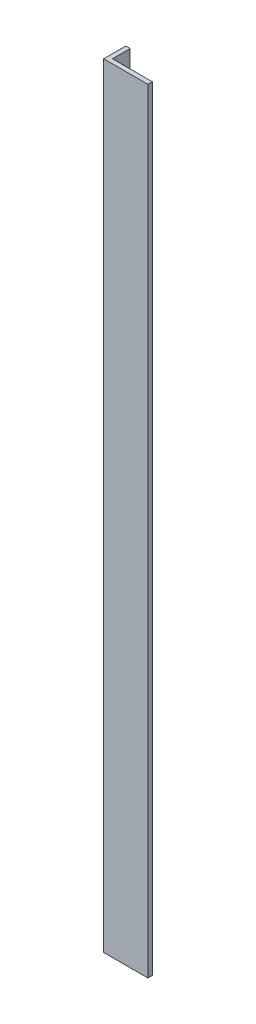
SolidWorks part; units mm, degrees
ref_plane "Front Plane" through (0, 0, 0) normal (0, 0, 1) x (1, 0, 0)
ref_plane "Top Plane" through (0, 0, 0) normal (0, 1, 0) x (1, 0, 0)
ref_plane "Right Plane" through (0, 0, 0) normal (1, 0, 0) x (0, 0, -1)
sketch "Sketch1" plane through (0, 0, 0) normal (0, 1, 0) x (1, 0, 0)
  line L0 (0, 0) -> (0, 10)
  line L1 (0, 10) -> (2, 10)
  line L2 (2, 10) -> (2, 2)
  line L3 (2, 2) -> (20, 2)
  line L4 (20, 2) -> (20, 0)
  line L5 (20, 0) -> (0, 0)
extrude "Boss-Extrude1" add sketch "Sketch1" along normal blind 300 and the other way up to surface (50 mm away)
hole_wizard "Ø3.0 (3) Diameter Hole3" positions "Sketch6" profile "Sketch7" hole size "Ø3.0" standard "ISO" end condition through all
sketch "Sketch6" plane through (2, 311.4076, -241.32) normal (1, 0, 0) x (0, 0, 1)
  point P0 (235.32, 355.4076)
  point P1 (235.32, 341.4076)
sketch "Sketch7" plane through (2, -44, -6) normal (0, 1, 0) x (0, 0, -1)
  line L0 (0, 0) -> (0, 2)
  line L1 (0, 2) -> (1.5, 2)
  line L2 (1.5, 2) -> (1.5, 0)
  line L3 (1.5, 0) -> (0, 0)
  line L4 (0, -6.35) -> (0, 107.95) construction
  dimension "Thru Hole Dia." = 3
  dimension "Thru Hole Depth" = 2
hole_wizard "Ø3.0 (3) Diameter Hole4" positions "Sketch8" profile "Sketch9" hole size "Ø3.0" standard "ISO" end condition through all
sketch "Sketch8" plane through (2, 311.4076, -241.32) normal (1, 0, 0) x (0, 0, 1)
  point P0 (235.32, 17.4076)
  point P1 (235.32, 31.4076)
sketch "Sketch9" plane through (2, 294, -6) normal (0, 1, 0) x (0, 0, -1)
  line L0 (0, 0) -> (0, 2)
  line L1 (0, 2) -> (1.5, 2)
  line L2 (1.5, 2) -> (1.5, 0)
  line L3 (1.5, 0) -> (0, 0)
  line L4 (0, -6.35) -> (0, 107.95) construction
  dimension "Thru Hole Dia." = 3
  dimension "Thru Hole Depth" = 2
